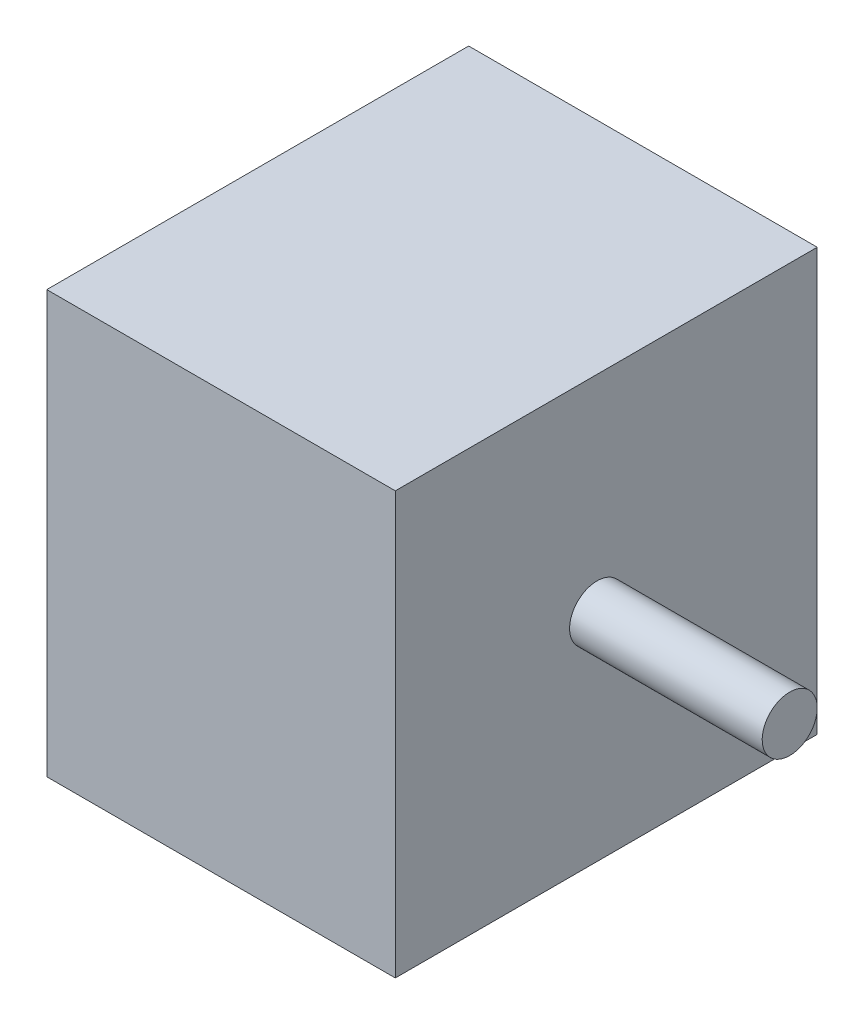
SolidWorks part; units mm, degrees
other "Marquage1"
sketch "Esquisse7" plane through (-22.1, 26.1, 52.2) normal (-0.1348, 0.2678, 0.954) x (-0.088, -0.9622, 0.2577)
ref_plane "Plan de face" through (0, 0, 0) normal (0, 0, 1) x (1, 0, 0)
ref_plane "Plan de dessus" through (0, 0, 0) normal (0, 1, 0) x (1, 0, 0)
ref_plane "Plan de droite" through (0, 0, 0) normal (1, 0, 0) x (0, 0, -1)
sketch "Esquisse1" plane through (0, 0, 0) normal (0, 0, 1) x (1, 0, 0)
  line L1 (-22.1, 26.1) -> (22.1, 26.1)
  line L2 (-22.1, 26.1) -> (-22.1, -26.1)
  line L3 (-22.1, -26.1) -> (22.1, -26.1)
  line L4 (22.1, 26.1) -> (22.1, -26.1)
  line L5 (-22.1, 26.1) -> (22.1, -26.1) construction
  line L6 (-22.1, -26.1) -> (22.1, 26.1) construction
  point P0 (0, 0)
  dimension "D1" = 44.2
  dimension "D2" = 52.2
extrude "Boss.-Extru.1" add sketch "Esquisse1" along normal blind 52.2
sketch "Esquisse2" plane through (22.1, 0, 0) normal (1, 0, 0) x (0, 0, -1)
  line L0 (-52.2, -19.9) -> (-28.55, -19.9)
  line L1 (-52.2, -26.1) -> (-52.2, 26.1) construction
  line L2 (-28.55, -19.9) -> (-28.55, -21.45)
  line L3 (-28.55, -21.45) -> (-32.25, -21.45)
  line L4 (-32.25, -21.45) -> (-32.25, -22.45)
  line L5 (-32.25, -22.45) -> (-28.7456, -26.1)
  line L6 (-52.2, -26.1) -> (0, -26.1) construction
  dimension "D1" = 23.65
  dimension "D2" = 6.2
  dimension "D3" = 1.55
  dimension "D4" = 3.7
  dimension "D5" = 1
  dimension "D6" = 5.06
extrude "Enlèv. mat.-Extru.2" cut sketch "Esquisse2" against normal blind 44.2 and the other way through all flip side to cut
sketch "Esquisse3" plane through (22.1, 0, 0) normal (1, 0, 0) x (0, 0, -1)
  line L0 (0, -19.9) -> (-23.65, -19.9)
  line L1 (0, -26.1) -> (0, 26.1) construction
  line L2 (-23.65, -19.9) -> (-23.65, -21.45)
  line L3 (-23.65, -21.45) -> (-19.95, -21.45)
  line L4 (-19.95, -21.45) -> (-19.95, -22.45)
  line L5 (-19.95, -22.45) -> (-23.4544, -26.1)
  line L6 (-28.7456, -26.1) -> (0, -26.1) construction
  dimension "D1" = 6.2
  dimension "D2" = 23.65
  dimension "D3" = 1.55
  dimension "D4" = 3.7
  dimension "D5" = 1
  dimension "D6" = 5.06
extrude "Enlèv. mat.-Extru.3" cut sketch "Esquisse3" against normal blind 44.2 and the other way through all
sketch "Esquisse4" plane through (0, 26.1, 0) normal (0, 1, 0) x (1, 0, 0)
  line L0 (-15.9, -52.2) -> (-15.9, -28.55)
  line L1 (22.1, -52.2) -> (-22.1, -52.2) construction
  line L2 (-15.9, -28.55) -> (-17.45, -28.55)
  line L3 (-17.45, -28.55) -> (-17.45, -32.25)
  line L4 (-17.45, -32.25) -> (-18.45, -32.25)
  line L5 (-18.45, -32.25) -> (-22.1, -28.7456)
  line L6 (-22.1, -52.2) -> (-22.1, 0) construction
  dimension "D1" = 6.2
  dimension "D2" = 23.65
  dimension "D3" = 1.55
  dimension "D4" = 3.7
  dimension "D5" = 1
  dimension "D6" = 5.06
extrude "Enlèv. mat.-Extru.4" cut sketch "Esquisse4" against normal blind 46 and the other way through all
sketch "Esquisse5" plane through (0, 26.1, 0) normal (0, 1, 0) x (1, 0, 0)
  line L0 (-15.9, 0) -> (-15.9, -23.65)
  line L1 (22.1, 0) -> (-22.1, 0) construction
  line L2 (-15.9, -23.65) -> (-17.45, -23.65)
  line L3 (-17.45, -23.65) -> (-17.45, -19.95)
  line L4 (-17.45, -19.95) -> (-18.45, -19.95)
  line L5 (-18.45, -19.95) -> (-22.1, -23.4544)
  line L6 (-22.1, -28.7456) -> (-22.1, 0) construction
  dimension "D1" = 6.2
  dimension "D2" = 23.65
  dimension "D3" = 1.55
  dimension "D4" = 3.7
  dimension "D5" = 1
  dimension "D6" = 5.06
extrude "Enlèv. mat.-Extru.5" cut sketch "Esquisse5" against normal blind 46 and the other way through all flip side to cut
sketch "Esquisse6" plane through (0, 0, 28.55) normal (0, 0, 1) x (1, 0, 0)
  line L0 (-22.1, -19.9) -> (-15.9, -19.9)
  line L1 (-15.9, -19.9) -> (-15.9, -26.0936)
extrude "Enlèv. mat.-Extru.7" cut sketch "Esquisse6" against normal through all both and the other way through all flip side to cut
sketch "Esquisse11" plane through (0, 26.1, 0) normal (0, 1, 0) x (1, 0, 0)
  line L0 (22.1, -52.2) -> (22.1, 0) construction
  line L1 (22.1, -49.1) -> (-15.9, -49.1)
  line L2 (-15.9, -28.55) -> (-15.9, -52.2) construction
  line L3 (22.1, -52.2) -> (-15.9, -52.2) construction
  dimension "D1" = 3.1
extrude "Enlèv. mat.-Extru.8" cut sketch "Esquisse11" against normal blind 46 and the other way through all
sketch "Esquisse12" plane through (0, 26.1, 0) normal (0, 1, 0) x (1, 0, 0)
  line L0 (22.1, -49.1) -> (22.1, 0) construction
  line L1 (22.1, -3.1) -> (-15.9, -3.1)
  line L2 (-15.9, -23.65) -> (-15.9, 0) construction
  line L3 (22.1, 0) -> (-15.9, 0) construction
  dimension "D1" = 3.1
extrude "Enlèv. mat.-Extru.9" cut sketch "Esquisse12" against normal blind 46 and the other way through all flip side to cut
sketch "Esquisse13" plane through (22.1, 0, 0) normal (1, 0, 0) x (0, 0, -1)
  line L0 (-28.55, -19.9) -> (-49.1, -19.9) construction
  line L1 (-3.1, 26.1) -> (-3.1, -19.9) construction
  circle A0 centre (-27.1, 3.6) radius 3
  dimension "D1" = 23.5
  dimension "D2" = 24
extrude "Boss.-Extru.2" add sketch "Esquisse13" along normal blind 21
sketch "Esquisse15" plane through (0, 26.1, 0) normal (0, 1, 0) x (1, 0, 0)
  line L0 (-15.9, -23.65) -> (-15.9, -28.55)
extrude "Enlèv. mat.-Extru.10" cut sketch "Esquisse15" against normal blind 49 and the other way through all flip side to cut
sketch "Esquisse16" plane through (-15.9, 0, 0) normal (-1, 0, 0) x (0, 0, 1)
  line L0 (23.65, -19.9) -> (28.55, -19.9)
extrude "Enlèv. mat.-Extru.11" cut sketch "Esquisse16" against normal blind 49 and the other way through all flip side to cut
